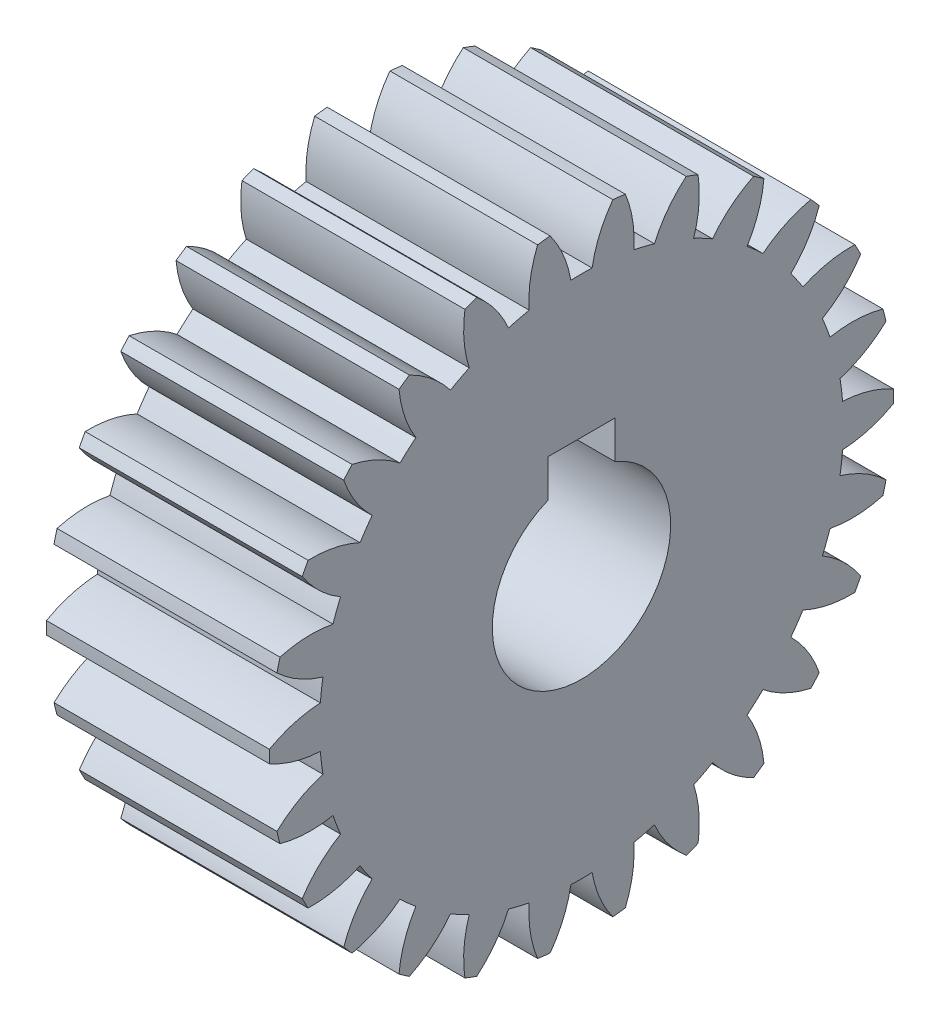
SolidWorks part; units mm, degrees
ref_plane "Plane1" through (0, 0, 0) normal (0, 0, 1) x (1, 0, 0)
ref_plane "Plane2" through (0, 0, 0) normal (0, 1, 0) x (1, 0, 0)
ref_plane "Plane3" through (0, 0, 0) normal (1, 0, 0) x (0, 0, -1)
other "Configuration Table"
sketch "HoldingSke" plane through (0, 0, 0) normal (0, 1, 0) x (1, 0, 0)
  line L0 (0, 0) -> (0.8988, -0.4384)
  line L1 (-15, 0) -> (100, 0) construction
  line L2 (0, 0) -> (-2.1039, 2.3779)
  line L3 (0, 0) -> (-11.863, 4.5341)
  line L4 (0, 0) -> (7.762, 3.7858)
  line L5 (0, 0) -> (-46.8476, -17.4728)
  line L6 (0, 0) -> (-8.2896, -5.593)
  line L7 (-2.1039, 2.3779) -> (8.6586, 51.2059)
  line L8 (-76.2, 54.61) -> (-74.8, 54.61)
  line L9 (-71.009, 38.7566) -> (-53.1078, 45.2721)
  line L10 (-76.2, 71.12) -> (104.1128, 71.12)
  line L11 (0, 0) -> (-10, 0)
  line L12 (-76.2, 101.6) -> (-76.162, 101.6)
  line L13 (24.9733, 27.94) -> (52.9518, 28.4284)
  line L14 (24.9733, 27.94) -> (24.9743, 27.94)
  line L15 (24.9733, 27.94) -> (100.4006, 29.5858)
  line L16 (-63.627, -1) -> (-12.827, -1)
  circle A0 centre (0, 0) radius 4
  circle A1 centre (0, 0) radius 11.749
  circle A2 centre (0, 0) radius 37.5
  circle A3 centre (0, 0) radius 4
  dimension "MHD" = 23.498
  dimension "Hub_dia" = 75
  dimension "Bore" = 8
  dimension "MBD" = 8
  dimension "Num_teeth" = 26
  dimension "Pitch" = 1
  dimension "Overall_len" = 50
  dimension "Show_teeth" = 26
  dimension "Thickness" = 10
  dimension "OAL" = 50.0001
  dimension "T_dim" = 1.4
  dimension "Ap" = 20
  dimension "H" = 19.05
  dimension "Pitch_radius" = 180.3128
  dimension "Width" = 10
  dimension "Backlash" = 0.038
  dimension "Addendum_fac" = 1
  dimension "Dedendum_fac" = 1.25
  dimension "Clearance_fac" = 0.25
  dimension "Dedendum_add" = 0.001
  dimension "Module" = 1
sketch "BasProSke" plane through (0, 0, 0) normal (0, 1, 0) x (1, 0, 0)
  line L0 (-10, 0) -> (60, 0) construction
  line L1 (0, 0) -> (0, 14)
  line L2 (0, 0) -> (10, 0)
  line L3 (10, 0) -> (10, 14)
  line L4 (10, 14) -> (0, 14)
  dimension "Thickness" = 10
  dimension "Diameter" = 28
revolve "Base-Revolve" add sketch "BasProSke" angle 360 about L0
sketch "TooCutSke" plane through (0, 0, 0) normal (1, 0, 0) x (0, 0, -1)
  line L1 (0, 0) -> (0, 107) construction
  line L2 (0, 0) -> (-0.8514, 12.9721) construction
  line L3 (0, 0) -> (-3.1292, 25.771) construction
  line L4 (-0.8514, 12.9721) -> (-1.5646, 12.8855) construction
  arc A0 (0.477, 11.7393) -> (-0.477, 11.7393) centre (0, 0) ccw
  arc A1 (1.4241, 13.9529) -> (-1.4241, 13.9529) centre (0, 0) ccw
  circle A2 centre (0, 0) radius 13 construction
  circle A3 centre (0, 0) radius 12.216 construction
  arc A4 (-0.477, 11.7393) -> (-1.4241, 13.9529) centre (-5.6014, 10.8561) ccw
  arc A5 (1.4241, 13.9529) -> (0.477, 11.7393) centre (5.6014, 10.8561) ccw
  dimension "Root_dia" = 23.498
  dimension "Overcut_dia" = 28.0508
  dimension "Pitch_dia" = 26
  dimension "Base_dia" = 24.432
  dimension "Flank_rad" = 5.2
  dimension "Half_ang" = 6.923
  dimension "Half_CT" = 0.7184
extrude "ToothCut" cut sketch "TooCutSke" along normal through all
fillet "Breaks" [suppressed] radius 0.02
fillet "RootFillets" [suppressed] radius 0.251
pattern_circular "TeethCuts" count 26 every 13.846 about axis through (-10, 0, 0) along (1, 0, 0) of "ToothCut", "RootFillets", "Breaks"
sketch "HubNeaOneSke" plane through (0, 0, 0) normal (-1, 0, 0) x (0, 0, 1)
  circle A0 centre (0, 0) radius 11.749
  dimension "Diameter" = 23.498
extrude "HubNearOne" [suppressed] add sketch "HubNeaOneSke" along normal blind 40.0001
sketch "HubNeaBotSke" plane through (0, 0, 0) normal (-1, 0, 0) x (0, 0, 1)
  circle A0 centre (0, 0) radius 11.749
  dimension "Diameter" = 23.498
extrude "HubNearBoth" [suppressed] add sketch "HubNeaBotSke" along normal blind 20
ref_plane "FarPln" through (10, 0, 0) normal (1, 0, 0) x (0, 0, -1)
sketch "HubFarSke" plane through (10, 0, 0) normal (1, 0, 0) x (0, 0, -1)
  circle A0 centre (0, 0) radius 11.749
  dimension "Diameter" = 23.498
extrude "HubFar" [suppressed] add sketch "HubFarSke" along normal blind 20
sketch "BorSke" plane through (0, 0, 0) normal (1, 0, 0) x (0, 0, -1)
  circle A0 centre (0, 0) radius 4
  dimension "Diameter" = 8
extrude "Bore" cut sketch "BorSke" along normal mid plane 100.0001
sketch "KeySke" plane through (0, 0, 0) normal (1, 0, 0) x (0, 0, -1)
  line L0 (-1.5, 0) -> (-1.5, 5.4)
  line L1 (-1.5, 5.4) -> (1.5, 5.4)
  line L2 (1.5, 5.4) -> (1.5, 0)
  line L3 (0, 0) -> (0, 34) construction
  line L4 (-1.5, 0) -> (1.5, 0)
  dimension "Offset" = 5.4
  dimension "Width" = 3
extrude "Keyway" cut sketch "KeySke" along normal mid plane 100.0001
pattern_circular "Keyway2" [suppressed] count 2 every 90 about axis through (-10, 0, 0) along (1, 0, 0)
equation "' \"Module@HoldingSke\" = 6.35"
equation "' \"Num_teeth@HoldingSke\" = 12"
equation "' \"Ap@HoldingSke\" =  20"
equation "' \"Ap@HoldingSke\" = 20"
equation "' \"Width@HoldingSke\" = 0.5 * 25.4"
equation "' \"Hub_dia@HoldingSke\"= 1 * 25.4"
equation "' \"Hub_dia@HoldingSke\" = 1 * 25.4"
equation "' \"Overall_len@HoldingSke\" = 1.0 * 25.4"
equation "' \"Bore@HoldingSke\" = 0.75 * 25.4"
equation "' \"T_dim@HoldingSke\" = 0.1 * 25.4"
equation "' \"Width@KeySke\" = 0.25 * 25.4"
equation "' \"Show_teeth@HoldingSke\" = 13"
equation "' \"Backlash@HoldingSke\" = 0.009 * 25.4"
equation "' \"Addendum_fac@HoldingSke\" = 1.0"
equation "' \"Dedendum_fac@HoldingSke\" = 1.25"
equation "' \"Dedendum_add@HoldingSke\" = 0.00005 * 25.4"
equation "' \"Clearance_fac@HoldingSke\" = 0.25"
equation "\"Pitch@HoldingSke\" = 1 / \"Module@HoldingSke\""
equation "\"Overcut_dia@TooCutSke\" = (\"Num_teeth@HoldingSke\" + 2 * \"Addendum_fac@HoldingSke\") / \"Pitch@HoldingSke\" + 0.002 * 25.4"
equation "\"Pitch_dia@TooCutSke\" = \"Num_teeth@HoldingSke\" / \"Pitch@HoldingSke\""
equation "\"Base_dia@TooCutSke\" = \"Num_teeth@HoldingSke\" / \"Pitch@HoldingSke\" * cos((\"Ap@HoldingSke\"  * 3.14159265 / 180))"
equation "\"Root_dia@TooCutSke\" = (\"Num_teeth@HoldingSke\" + 2) / \"Pitch@HoldingSke\" - 2 * (\"Addendum_fac@HoldingSke\" + \"Dedendum_fac@HoldingSke\") / \"Pitch@HoldingSke\" - \"Dedendum_add@HoldingSke\" * 2"
equation "\"Half_ang@TooCutSke\" = 180 / \"Num_teeth@HoldingSke\""
equation "\"Half_CT@TooCutSke\" = \"Num_teeth@HoldingSke\" / \"Pitch@HoldingSke\" * sin((3.14159265 / 2 / \"Num_teeth@HoldingSke\")) / 2 - 7 * \"Backlash@HoldingSke\" / 4"
equation "\"Flank_rad@TooCutSke\" = \"Num_teeth@HoldingSke\" / \"Pitch@HoldingSke\" / 5"
equation "\"Radius@RootFillets\" = \"Clearance_fac@HoldingSke\" / \"Pitch@HoldingSke\" + \"Dedendum_add@HoldingSke\""
equation "\"Break_rad@Breaks\" = 0.02 / \"Pitch@HoldingSke\""
equation "\"Thickness@HoldingSke\" = \"Width@HoldingSke\""
equation "\"OAL@HoldingSke\" = \"Thickness@HoldingSke\""
equation "\"MHD@HoldingSke\" = (\"Num_teeth@HoldingSke\" + 2) / \"Pitch@HoldingSke\" - 2 * (\"Addendum_fac@HoldingSke\" + \"Dedendum_fac@HoldingSke\")  / \"Pitch@HoldingSke\" - \"Dedendum_add@HoldingSke\" * 2"
equation "\"MBD@HoldingSke\" = (\"Num_teeth@HoldingSke\" + 2) / \"Pitch@HoldingSke\" - 2 * (\"Addendum_fac@HoldingSke\" + \"Dedendum_fac@HoldingSke\")  / \"Pitch@HoldingSke\" - \"Dedendum_add@HoldingSke\" * 2 - 0.002 * 25.4"
equation "\"MHD@HoldingSke\" = ((sgn( \"MHD@HoldingSke\" - \"Hub_dia@HoldingSke\" )-1)*( \"MHD@HoldingSke\" - \"Hub_dia@HoldingSke\" ))/-2+ \"Hub_dia@HoldingSke\""
equation "\"MBD@HoldingSke\" = ((sgn( \"MBD@HoldingSke\" - \"Bore@HoldingSke\" )-1)*( \"MBD@HoldingSke\" - \"Bore@HoldingSke\" ))/-2+ \"Bore@HoldingSke\""
equation "\"OAL@HoldingSke\" = ((sgn( \"OAL@HoldingSke\" - \"Overall_len@HoldingSke\" )+1)*( \"OAL@HoldingSke\" - \"Overall_len@HoldingSke\" ))/2 + \"Overall_len@HoldingSke\" + 0.000002 * 25.4"
equation "\"Num_teeth@TeethCuts\" = int( \"Show_teeth@HoldingSke\" ) + 1"
equation "\"Num_teeth@TeethCuts\" = ((sgn( \"Num_teeth@TeethCuts\" - \"Num_teeth@HoldingSke\" )-1)*( \"Num_teeth@TeethCuts\" - \"Num_teeth@HoldingSke\" ))/-2+ \"Num_teeth@HoldingSke\""
equation "\"Num_teeth@TeethCuts\" = ((sgn( \"Num_teeth@TeethCuts\" - 2.0)+1)*( \"Num_teeth@TeethCuts\" - 2.0))/2 +2.0"
equation "\"Angle@TeethCuts\" = 360.0 / \"Num_teeth@HoldingSke\""
equation "\"Diameter@BasProSke\" = (\"Num_teeth@HoldingSke\" + 2 * \"Addendum_fac@HoldingSke\") / \"Pitch@HoldingSke\""
equation "\"Thickness@BasProSke\"  = \"Thickness@HoldingSke\""
equation "' \"Fillet_rad@BasProSke\" =  \"Thickness@HoldingSke\" * 0.05"
equation "' \"Fillet_rad@BasProSke\" = \"Thickness@HoldingSke\" * 0.05"
equation "\"MHD@HoldingSke\" = ((sgn( \"MHD@HoldingSke\" - \"Root_dia@TooCutSke\" )-1)*( \"MHD@HoldingSke\" - \"Root_dia@TooCutSke\" ))/-2+ \"Root_dia@TooCutSke\""
equation "\"Diameter@HubNeaOneSke\" = \"MHD@HoldingSke\""
equation "\"Length@HubNearOne\" = \"OAL@HoldingSke\" - \"Thickness@BasProSke\""
equation "\"Diameter@HubNeaBotSke\" = \"MHD@HoldingSke\""
equation "\"Length@HubNearBoth\" = ( \"OAL@HoldingSke\" - \"Thickness@BasProSke\" ) / 2.0"
equation "\"Thickness@FarPln\" = \"Thickness@BasProSke\""
equation "\"Diameter@HubFarSke\" = \"MHD@HoldingSke\""
equation "\"Length@HubFar\" = ( \"OAL@HoldingSke\" - \"Thickness@BasProSke\" ) / 2.0"
equation "\"Diameter@BorSke\" = \"MBD@HoldingSke\""
equation "\"D1@Bore\" = \"OAL@HoldingSke\" * 2.0"
equation "\"D1@Keyway\" = \"OAL@HoldingSke\" * 2.0"
equation "\"Offset@KeySke\" = \"T_dim@HoldingSke\" + \"MBD@HoldingSke\" / 2.0"
